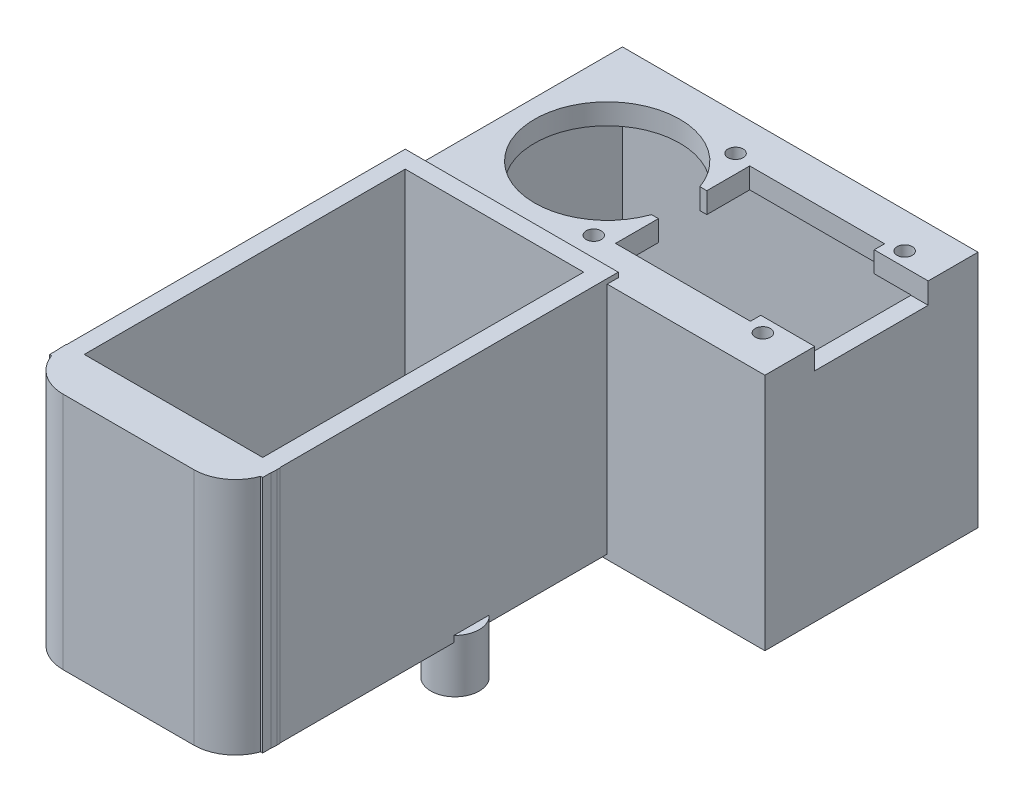
SolidWorks part; units mm, degrees
ref_plane "Front Plane" through (0, 0, 0) normal (0, 0, 1) x (1, 0, 0)
ref_plane "Top Plane" through (0, 0, 0) normal (0, 1, 0) x (1, 0, 0)
ref_plane "Right Plane" through (0, 0, 0) normal (1, 0, 0) x (0, 0, -1)
ref_plane "PZ_m38_200" through (0, 0, -38.2) normal (0, 0, 1) x (1, 0, 0)
sketch "S_box1" plane through (0, 0, -38.2) normal (0, 0, 1) x (1, 0, 0)
  line L0 (-15.4, -37.4) -> (15.4, -37.4)
  line L1 (15.4, -37.4) -> (15.4, -2.9)
  line L2 (15.4, -2.9) -> (-15.4, -2.9)
  line L3 (-15.4, -2.9) -> (-15.4, -37.4)
  dimension "P1" = 15.4
  dimension "P2" = 37.4
  dimension "P3" = 15.4
  dimension "P4" = 37.4
  dimension "P5" = 15.4
  dimension "P6" = 2.9
  dimension "P7" = 15.4
  dimension "P8" = 2.9
extrude "Boss_1" add sketch "S_box1" along normal blind 2.5
ref_plane "PZ_p10_700" through (0, 0, 10.7) normal (0, 0, 1) x (1, 0, 0)
sketch "S_box2" plane through (0, 0, 10.7) normal (0, 0, 1) x (1, 0, 0)
  line L0 (-15.4, -37.4) -> (15.4, -37.4)
  line L1 (15.4, -37.4) -> (15.4, -2.9)
  line L2 (15.4, -2.9) -> (-15.4, -2.9)
  line L3 (-15.4, -2.9) -> (-15.4, -37.4)
  dimension "P1" = 15.4
  dimension "P2" = 37.4
  dimension "P3" = 15.4
  dimension "P4" = 37.4
  dimension "P5" = 15.4
  dimension "P6" = 2.9
  dimension "P7" = 15.4
  dimension "P8" = 2.9
extrude "Boss_2" add sketch "S_box2" along normal blind 2.5
sketch "S_box3" plane through (0, 0, -38.2) normal (0, 0, 1) x (1, 0, 0)
  line L0 (-15.4, -37.4) -> (-12.9, -37.4)
  line L1 (-12.9, -37.4) -> (-12.9, -2.9)
  line L2 (-12.9, -2.9) -> (-15.4, -2.9)
  line L3 (-15.4, -2.9) -> (-15.4, -37.4)
  dimension "P1" = 15.4
  dimension "P2" = 37.4
  dimension "P3" = 12.9
  dimension "P4" = 37.4
  dimension "P5" = 12.9
  dimension "P6" = 2.9
  dimension "P7" = 15.4
  dimension "P8" = 2.9
extrude "Boss_3" add sketch "S_box3" along normal blind 51.4
sketch "S_box4" plane through (0, 0, -38.2) normal (0, 0, 1) x (1, 0, 0)
  line L0 (12.9, -37.4) -> (15.4, -37.4)
  line L1 (15.4, -37.4) -> (15.4, -2.9)
  line L2 (15.4, -2.9) -> (12.9, -2.9)
  line L3 (12.9, -2.9) -> (12.9, -37.4)
  dimension "P1" = 12.9
  dimension "P2" = 37.4
  dimension "P3" = 15.4
  dimension "P4" = 37.4
  dimension "P5" = 15.4
  dimension "P6" = 2.9
  dimension "P7" = 12.9
  dimension "P8" = 2.9
extrude "Boss_4" add sketch "S_box4" along normal blind 51.4
sketch "S_box5" plane through (0, 0, -38.2) normal (0, 0, 1) x (1, 0, 0)
  line L0 (-15.4, -37.4) -> (15.4, -37.4)
  line L1 (15.4, -37.4) -> (15.4, -34.4)
  line L2 (15.4, -34.4) -> (-15.4, -34.4)
  line L3 (-15.4, -34.4) -> (-15.4, -37.4)
  dimension "P1" = 15.4
  dimension "P2" = 37.4
  dimension "P3" = 15.4
  dimension "P4" = 37.4
  dimension "P5" = 15.4
  dimension "P6" = 34.4
  dimension "P7" = 15.4
  dimension "P8" = 34.4
extrude "Boss_5" add sketch "S_box5" along normal blind 51.4
ref_plane "PZ_m67_400" through (0, 0, -67.4) normal (0, 0, 1) x (1, 0, 0)
sketch "S_box6" plane through (0, 0, -67.4) normal (0, 0, 1) x (1, 0, 0)
  line L0 (-13.2, -38.1) -> (-10.7, -38.1)
  line L1 (-10.7, -38.1) -> (-10.7, -3.6)
  line L2 (-10.7, -3.6) -> (-13.2, -3.6)
  line L3 (-13.2, -3.6) -> (-13.2, -38.1)
  dimension "P1" = 13.2
  dimension "P2" = 38.1
  dimension "P3" = 10.7
  dimension "P4" = 38.1
  dimension "P5" = 10.7
  dimension "P6" = 3.6
  dimension "P7" = 13.2
  dimension "P8" = 3.6
extrude "Boss_6" add sketch "S_box6" along normal blind 30.8
sketch "S_box7" plane through (0, 0, -67.4) normal (0, 0, 1) x (1, 0, 0)
  line L0 (35.7, -38.1) -> (38.2, -38.1)
  line L1 (38.2, -38.1) -> (38.2, -3.6)
  line L2 (38.2, -3.6) -> (35.7, -3.6)
  line L3 (35.7, -3.6) -> (35.7, -38.1)
  dimension "P1" = 35.7
  dimension "P2" = 38.1
  dimension "P3" = 38.2
  dimension "P4" = 38.1
  dimension "P5" = 38.2
  dimension "P6" = 3.6
  dimension "P7" = 35.7
  dimension "P8" = 3.6
extrude "Boss_7" add sketch "S_box7" along normal blind 30.8
sketch "S_box8" plane through (0, 0, -67.4) normal (0, 0, 1) x (1, 0, 0)
  line L0 (-13.2, -38.1) -> (38.2, -38.1)
  line L1 (38.2, -38.1) -> (38.2, -3.6)
  line L2 (38.2, -3.6) -> (-13.2, -3.6)
  line L3 (-13.2, -3.6) -> (-13.2, -38.1)
  dimension "P1" = 13.2
  dimension "P2" = 38.1
  dimension "P3" = 38.2
  dimension "P4" = 38.1
  dimension "P5" = 38.2
  dimension "P6" = 3.6
  dimension "P7" = 13.2
  dimension "P8" = 3.6
extrude "Boss_8" add sketch "S_box8" along normal blind 2.5
ref_plane "PZ_m39_100" through (0, 0, -39.1) normal (0, 0, 1) x (1, 0, 0)
sketch "S_box9" plane through (0, 0, -39.1) normal (0, 0, 1) x (1, 0, 0)
  line L0 (-13.2, -38.1) -> (38.2, -38.1)
  line L1 (38.2, -38.1) -> (38.2, -3.6)
  line L2 (38.2, -3.6) -> (-13.2, -3.6)
  line L3 (-13.2, -3.6) -> (-13.2, -38.1)
  dimension "P1" = 13.2
  dimension "P2" = 38.1
  dimension "P3" = 38.2
  dimension "P4" = 38.1
  dimension "P5" = 38.2
  dimension "P6" = 3.6
  dimension "P7" = 13.2
  dimension "P8" = 3.6
extrude "Boss_9" add sketch "S_box9" along normal blind 2.5
sketch "S_box10" plane through (0, 0, -67.4) normal (0, 0, 1) x (1, 0, 0)
  line L0 (-13.2, -6.6) -> (38.2, -6.6)
  line L1 (38.2, -6.6) -> (38.2, -3.6)
  line L2 (38.2, -3.6) -> (-13.2, -3.6)
  line L3 (-13.2, -3.6) -> (-13.2, -6.6)
  dimension "P1" = 13.2
  dimension "P2" = 6.6
  dimension "P3" = 38.2
  dimension "P4" = 6.6
  dimension "P5" = 38.2
  dimension "P6" = 3.6
  dimension "P7" = 13.2
  dimension "P8" = 3.6
extrude "Boss_10" add sketch "S_box10" along normal blind 30.8
ref_plane "PY_m37_400" through (0, -37.4, 0) normal (0, 1, 0) x (1, 0, 0)
sketch "S_prism11" plane through (0, -37.4, 0) normal (0, 1, 0) x (1, 0, 0)
  line L0 (-15.45, -10.75) -> (15.45, -10.75)
  line L1 (15.45, -10.75) -> (15.45, -11.2)
  line L2 (9.45, -17.2) -> (-9.45, -17.2)
  line L3 (-15.45, -11.2) -> (-15.45, -10.75)
  arc A0 (15.45, -11.2) -> (9.45, -17.2) centre (9.4499, -11.1999) cw
  arc A1 (-9.45, -17.2) -> (-15.45, -11.2) centre (-9.4499, -11.1999) cw
extrude "Boss_11" add sketch "S_prism11" along normal blind 34.5
ref_plane "PY_m44_200" through (0, -44.2, 0) normal (0, 1, 0) x (1, 0, 0)
sketch "S_cyl12" plane through (0, -44.2, 0) normal (0, 1, 0) x (1, 0, 0)
  circle A0 centre (13, 17) radius 3.5
  dimension "D1_S_cyl12" = 7
  dimension "P2" = 13
  dimension "P3" = 17
extrude "Boss_12" add sketch "S_cyl12" along normal blind 7.7
ref_plane "PY_m37_500" through (0, -37.5, 0) normal (0, 1, 0) x (1, 0, 0)
sketch "S_hole13" plane through (0, -37.5, 0) normal (0, 1, 0) x (1, 0, 0)
  circle A0 centre (0, 0) radius 10.5
  dimension "D1_S_hole13" = 21
extrude "Hole_13" cut sketch "S_hole13" along normal blind 3.2
ref_plane "PZ_m30_400" through (0, 0, -30.4) normal (0, 0, 1) x (1, 0, 0)
sketch "S_cut14" plane through (0, 0, -30.4) normal (0, 0, 1) x (1, 0, 0)
  line L0 (-9.7, -37.5) -> (9.7, -37.5)
  line L1 (9.7, -37.5) -> (9.7, -34.35)
  line L2 (9.7, -34.35) -> (-9.7, -34.35)
  line L3 (-9.7, -34.35) -> (-9.7, -37.5)
  dimension "P1" = 9.7
  dimension "P2" = 37.5
  dimension "P3" = 9.7
  dimension "P4" = 37.5
  dimension "P5" = 9.7
  dimension "P6" = 34.35
  dimension "P7" = 9.7
  dimension "P8" = 34.35
extrude "Pocket_14" cut sketch "S_cut14" along normal blind 19.5
ref_plane "PZ_m38_700" through (0, 0, -38.7) normal (0, 0, 1) x (1, 0, 0)
sketch "S_cut15" plane through (0, 0, -38.7) normal (0, 0, 1) x (1, 0, 0)
  line L0 (-8.2, -37.5) -> (8.2, -37.5)
  line L1 (8.2, -37.5) -> (8.2, -34.35)
  line L2 (8.2, -34.35) -> (-8.2, -34.35)
  line L3 (-8.2, -34.35) -> (-8.2, -37.5)
  dimension "P1" = 8.2
  dimension "P2" = 37.5
  dimension "P3" = 8.2
  dimension "P4" = 37.5
  dimension "P5" = 8.2
  dimension "P6" = 34.35
  dimension "P7" = 8.2
  dimension "P8" = 34.35
extrude "Pocket_15" cut sketch "S_cut15" along normal blind 8.3
ref_plane "PZ_m11_000" through (0, 0, -11) normal (0, 0, 1) x (1, 0, 0)
sketch "S_cut16" plane through (0, 0, -11) normal (0, 0, 1) x (1, 0, 0)
  line L0 (-3.5, -37.5) -> (3.5, -37.5)
  line L1 (3.5, -37.5) -> (3.5, -34.35)
  line L2 (3.5, -34.35) -> (-3.5, -34.35)
  line L3 (-3.5, -34.35) -> (-3.5, -37.5)
  dimension "P1" = 3.5
  dimension "P2" = 37.5
  dimension "P3" = 3.5
  dimension "P4" = 37.5
  dimension "P5" = 3.5
  dimension "P6" = 34.35
  dimension "P7" = 3.5
  dimension "P8" = 34.35
extrude "Pocket_16" cut sketch "S_cut16" along normal blind 11
sketch "S_hole17" plane through (0, -37.5, 0) normal (0, 1, 0) x (1, 0, 0)
  circle A0 centre (-10.25, 8.3) radius 1.1
  dimension "D1_S_hole17" = 2.2
  dimension "P2" = 10.25
  dimension "P3" = 8.3
extrude "Hole_17" cut sketch "S_hole17" along normal blind 3.2
sketch "S_hole18" plane through (0, -37.5, 0) normal (0, 1, 0) x (1, 0, 0)
  circle A0 centre (10.25, 8.3) radius 1.1
  dimension "D1_S_hole18" = 2.2
  dimension "P2" = 10.25
  dimension "P3" = 8.3
extrude "Hole_18" cut sketch "S_hole18" along normal blind 3.2
sketch "S_hole19" plane through (0, -37.5, 0) normal (0, 1, 0) x (1, 0, 0)
  circle A0 centre (-10.25, 32.75) radius 1.1
  dimension "D1_S_hole19" = 2.2
  dimension "P2" = 10.25
  dimension "P3" = 32.75
extrude "Hole_19" cut sketch "S_hole19" along normal blind 3.2
sketch "S_hole20" plane through (0, -37.5, 0) normal (0, 1, 0) x (1, 0, 0)
  circle A0 centre (10.25, 32.75) radius 1.1
  dimension "D1_S_hole20" = 2.2
  dimension "P2" = 10.25
  dimension "P3" = 32.75
extrude "Hole_20" cut sketch "S_hole20" along normal blind 3.2
ref_plane "PY_m6_700" through (0, -6.7, 0) normal (0, 1, 0) x (1, 0, 0)
sketch "S_hole21" plane through (0, -6.7, 0) normal (0, 1, 0) x (1, 0, 0)
  circle A0 centre (0, 52) radius 10.5
  dimension "D1_S_hole21" = 21
  dimension "P2" = 52
extrude "Hole_21" cut sketch "S_hole21" along normal blind 3.2
ref_plane "PZ_m61_700" through (0, 0, -61.7) normal (0, 0, 1) x (1, 0, 0)
sketch "S_cut22" plane through (0, 0, -61.7) normal (0, 0, 1) x (1, 0, 0)
  line L0 (10.9, -6.65) -> (30.4, -6.65)
  line L1 (30.4, -6.65) -> (30.4, -3.5)
  line L2 (30.4, -3.5) -> (10.9, -3.5)
  line L3 (10.9, -3.5) -> (10.9, -6.65)
  dimension "P1" = 10.9
  dimension "P2" = 6.65
  dimension "P3" = 30.4
  dimension "P4" = 6.65
  dimension "P5" = 30.4
  dimension "P6" = 3.5
  dimension "P7" = 10.9
  dimension "P8" = 3.5
extrude "Pocket_22" cut sketch "S_cut22" along normal blind 19.4
ref_plane "PZ_m60_200" through (0, 0, -60.2) normal (0, 0, 1) x (1, 0, 0)
sketch "S_cut23" plane through (0, 0, -60.2) normal (0, 0, 1) x (1, 0, 0)
  line L0 (30.4, -6.65) -> (38.7, -6.65)
  line L1 (38.7, -6.65) -> (38.7, -3.5)
  line L2 (38.7, -3.5) -> (30.4, -3.5)
  line L3 (30.4, -3.5) -> (30.4, -6.65)
  dimension "P1" = 30.4
  dimension "P2" = 6.65
  dimension "P3" = 38.7
  dimension "P4" = 6.65
  dimension "P5" = 38.7
  dimension "P6" = 3.5
  dimension "P7" = 30.4
  dimension "P8" = 3.5
extrude "Pocket_23" cut sketch "S_cut23" along normal blind 16.4
ref_plane "PZ_m55_500" through (0, 0, -55.5) normal (0, 0, 1) x (1, 0, 0)
sketch "S_cut24" plane through (0, 0, -55.5) normal (0, 0, 1) x (1, 0, 0)
  line L0 (0, -6.65) -> (11, -6.65)
  line L1 (11, -6.65) -> (11, -3.5)
  line L2 (11, -3.5) -> (0, -3.5)
  line L3 (0, -3.5) -> (0, -6.65)
  dimension "P1" = 6.65
  dimension "P2" = 11
  dimension "P3" = 6.65
  dimension "P4" = 11
  dimension "P5" = 3.5
  dimension "P6" = 3.5
extrude "Pocket_24" cut sketch "S_cut24" along normal blind 7
sketch "S_hole25" plane through (0, -6.7, 0) normal (0, 1, 0) x (1, 0, 0)
  circle A0 centre (8.3, 62.25) radius 1.1
  dimension "D1_S_hole25" = 2.2
  dimension "P2" = 8.3
  dimension "P3" = 62.25
extrude "Hole_25" cut sketch "S_hole25" along normal blind 3.2
sketch "S_hole26" plane through (0, -6.7, 0) normal (0, 1, 0) x (1, 0, 0)
  circle A0 centre (8.3, 41.75) radius 1.1
  dimension "D1_S_hole26" = 2.2
  dimension "P2" = 8.3
  dimension "P3" = 41.75
extrude "Hole_26" cut sketch "S_hole26" along normal blind 3.2
sketch "S_hole27" plane through (0, -6.7, 0) normal (0, 1, 0) x (1, 0, 0)
  circle A0 centre (32.75, 62.25) radius 1.1
  dimension "D1_S_hole27" = 2.2
  dimension "P2" = 32.75
  dimension "P3" = 62.25
extrude "Hole_27" cut sketch "S_hole27" along normal blind 3.2
sketch "S_hole28" plane through (0, -6.7, 0) normal (0, 1, 0) x (1, 0, 0)
  circle A0 centre (32.75, 41.75) radius 1.1
  dimension "D1_S_hole28" = 2.2
  dimension "P2" = 32.75
  dimension "P3" = 41.75
extrude "Hole_28" cut sketch "S_hole28" along normal blind 3.2
equation "\"plate_t\" = 3"
equation "\"clearance\" = 0.5"
